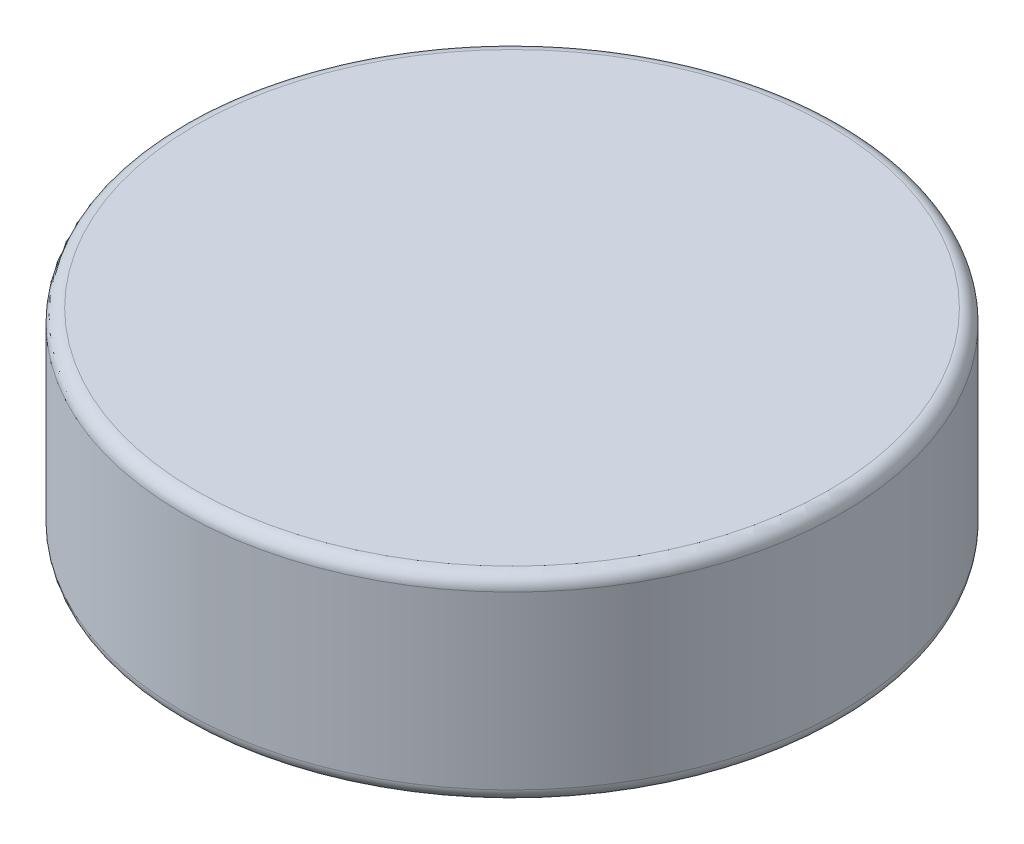
SolidWorks part; units mm, degrees
ref_plane "Front Plane" through (0, 0, 0) normal (0, 0, 1) x (1, 0, 0)
ref_plane "Top Plane" through (0, 0, 0) normal (0, 1, 0) x (1, 0, 0)
ref_plane "Right Plane" through (0, 0, 0) normal (1, 0, 0) x (0, 0, -1)
sketch "Sketch1" plane through (0, 0, 0) normal (0, 1, 0) x (1, 0, 0)
  circle A0 centre (0, 0) radius 5
  dimension "D1" = 10
extrude "Boss-Extrude1" add sketch "Sketch1" along normal mid plane 3
fillet "Fillet1" radius 0.2 2 edges at (0, -1.5, 5) (0, 1.5, 5)
